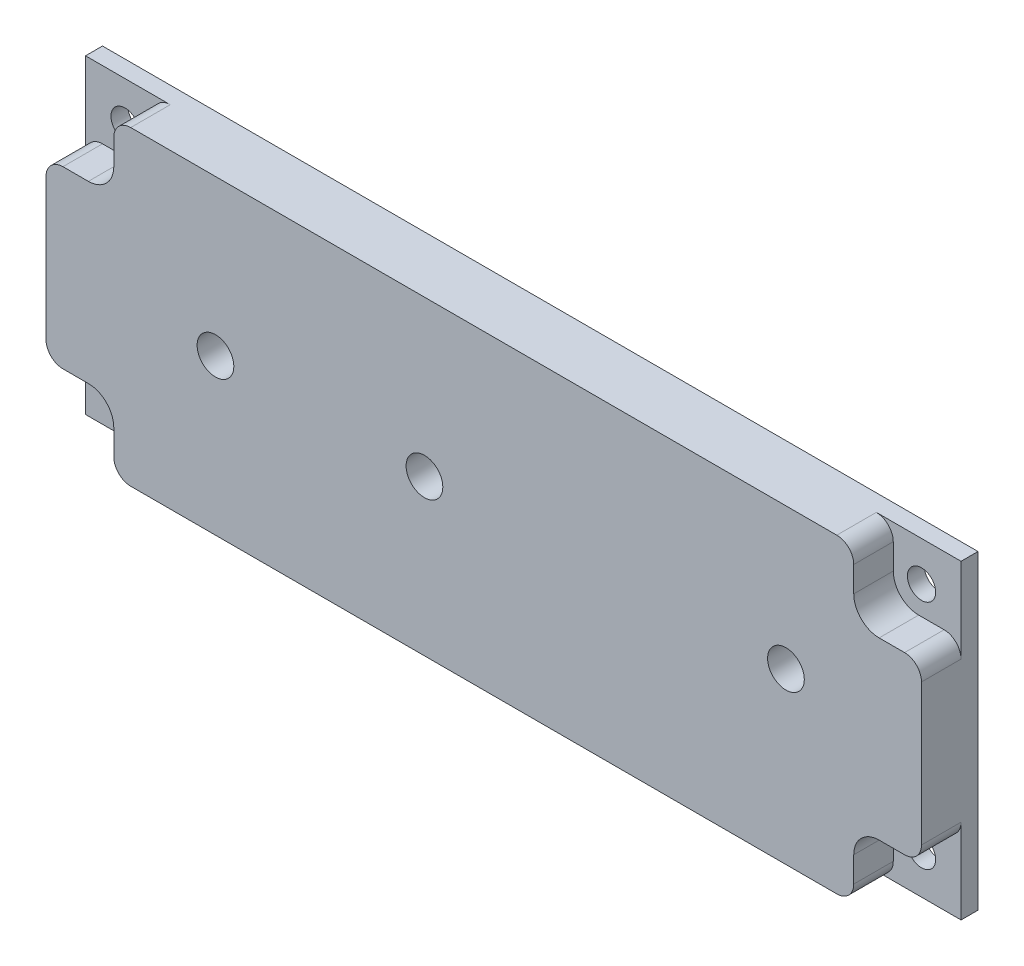
SolidWorks part; units mm, degrees
ref_plane "Front Plane" through (0, 0, 0) normal (0, 0, 1) x (1, 0, 0)
ref_plane "Top Plane" through (0, 0, 0) normal (0, 1, 0) x (1, 0, 0)
ref_plane "Right Plane" through (0, 0, 0) normal (1, 0, 0) x (0, 0, -1)
sketch "Sketch1" plane through (0, 0, 0) normal (0, 0, 1) x (1, 0, 0)
  line L1 (-75.3429, 31.5404) -> (79.6571, 31.5404)
  line L2 (-75.3429, 31.5404) -> (-75.3429, -23.4596)
  line L3 (-75.3429, -23.4596) -> (79.6571, -23.4596)
  line L4 (79.6571, 31.5404) -> (79.6571, -23.4596)
  circle A0 centre (-45.3429, 4.0404) radius 3.25
  circle A1 centre (-8.3429, 4.0404) radius 3.25
  circle A2 centre (55.6571, 6.5404) radius 3.25
  dimension "D5" = 6.5
  dimension "D6" = 6.5
  dimension "D11" = 6.5
  dimension "D1" = 155
  dimension "D2" = 55
  dimension "D3" = 27.5
  dimension "D4" = 27.5
  dimension "D7" = 30
  dimension "D8" = 37
  dimension "D9" = 24
  dimension "D10" = 25
extrude "Boss-Extrude1" add sketch "Sketch1" along normal blind 10
sketch "Sketch2" plane through (0, 0, 10) normal (0, 0, 1) x (1, 0, 0)
  line L1 (-75.3429, 31.5404) -> (-63.3429, 31.5404)
  line L2 (-75.3429, 31.5404) -> (-75.3429, 19.5404)
  line L3 (-75.3429, 19.5404) -> (-67.8429, 19.5404)
  line L4 (-63.3429, 31.5404) -> (-63.3429, 24.0404)
  line L5 (-75.3429, -23.4596) -> (-63.3429, -23.4596)
  line L6 (-75.3429, -23.4596) -> (-75.3429, -11.4596)
  line L7 (-75.3429, -11.4596) -> (-67.8429, -11.4596)
  line L8 (-63.3429, -23.4596) -> (-63.3429, -15.9596)
  line L9 (79.6571, -23.4596) -> (67.6571, -23.4596)
  line L10 (79.6571, -23.4596) -> (79.6571, -11.4596)
  line L11 (79.6571, -11.4596) -> (72.1571, -11.4596)
  line L12 (67.6571, -23.4596) -> (67.6571, -15.9596)
  line L13 (79.6571, 31.5404) -> (67.6571, 31.5404)
  line L14 (79.6571, 31.5404) -> (79.6571, 19.5404)
  line L15 (79.6571, 19.5404) -> (72.1571, 19.5404)
  line L16 (67.6571, 31.5404) -> (67.6571, 24.0404)
  arc A0 (67.6571, 24.0404) -> (72.1571, 19.5404) centre (72.1571, 24.0404) ccw
  arc A1 (72.1571, -11.4596) -> (67.6571, -15.9596) centre (72.1571, -15.9596) ccw
  arc A2 (-63.3429, -15.9596) -> (-67.8429, -11.4596) centre (-67.8429, -15.9596) ccw
  arc A3 (-63.3429, 24.0404) -> (-67.8429, 19.5404) centre (-67.8429, 24.0404) cw
  point P22 (67.6571, 19.5404)
  point P25 (67.6571, -11.4596)
  point P28 (-63.3429, -11.4596)
  point P31 (-63.3429, 19.5404)
  dimension "D9" = 4.5
  dimension "D1" = 12
  dimension "D2" = 12
  dimension "D3" = 12
  dimension "D4" = 12
  dimension "D5" = 12
  dimension "D6" = 12
  dimension "D7" = 12
  dimension "D8" = 12
extrude "Cut-Extrude1" cut sketch "Sketch2" against normal blind 7
sketch "Sketch3" plane through (0, 0, 3) normal (0, 0, 1) x (1, 0, 0)
  line L0 (-67.8429, -11.4596) -> (-75.3429, -11.4596) construction
  line L1 (67.6571, -15.9596) -> (67.6571, -23.4596) construction
  line L2 (79.6571, -11.4596) -> (72.1571, -11.4596) construction
  line L3 (72.1571, 19.5404) -> (79.6571, 19.5404) construction
  line L4 (67.6571, 31.5404) -> (67.6571, 24.0404) construction
  line L7 (-75.3429, 19.5404) -> (-67.8429, 19.5404) construction
  line L9 (-63.3429, 24.0404) -> (-63.3429, 31.5404) construction
  circle A0 centre (-68.3429, -16.4596) radius 2.5
  circle A1 centre (72.6571, -16.4596) radius 2.5
  circle A2 centre (72.6571, 24.5404) radius 2.5
  circle A5 centre (-68.3429, 24.5404) radius 2.5
  dimension "D1" = 5
  dimension "D4" = 5
  dimension "D7" = 5
  dimension "D10" = 5
  dimension "D2" = 5
  dimension "D3" = 5
  dimension "D5" = 5
  dimension "D6" = 5
  dimension "D8" = 5
  dimension "D9" = 5
  dimension "D11" = 5
  dimension "D12" = 5
extrude "Cut-Extrude2" cut sketch "Sketch3" against normal blind 10
fillet "Fillet1" radius 3 8 edges at (67.6571, 31.5404, 6.5) (79.6571, 19.5404, 6.5) (79.6571, -11.4596, 6.5) (67.6571, -23.4596, 6.5) (-63.3429, 31.5404, 6.5) (-75.3429, 19.5404, 6.5) (-63.3429, -23.4596, 6.5) (-75.3429, -11.4596, 6.5)
